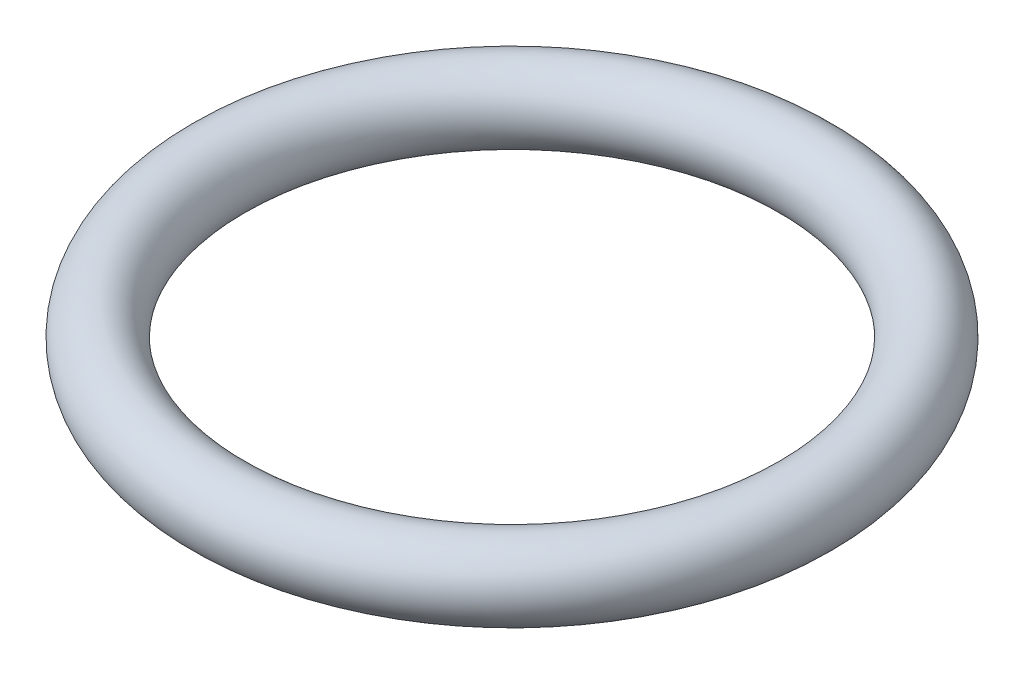
SolidWorks part; units mm, degrees
ref_plane "Front Plane" through (0, 0, 0) normal (0, 0, 1) x (1, 0, 0)
ref_plane "Top Plane" through (0, 0, 0) normal (0, 1, 0) x (1, 0, 0)
ref_plane "Right Plane" through (0, 0, 0) normal (1, 0, 0) x (0, 0, -1)
sketch "Sketch2" plane through (0, 0, 0) normal (0, 0, 1) x (1, 0, 0)
  line L0 (0, 4.9966) -> (0, -6.2527) construction
  circle A0 centre (14.26, 0) radius 1.78
  dimension "D1" = 14.26
  dimension "D2" = 3.56
  dimension "D3" = 0
revolve "Revolve1" add sketch "Sketch2" angle 360 about L0
sketch "Sketch4" plane through (0, 0, 0) normal (0, 1, 0) x (1, 0, 0)
  circle A0 centre (0, 0) radius 14.26 construction
  dimension "D1" = 28.52
